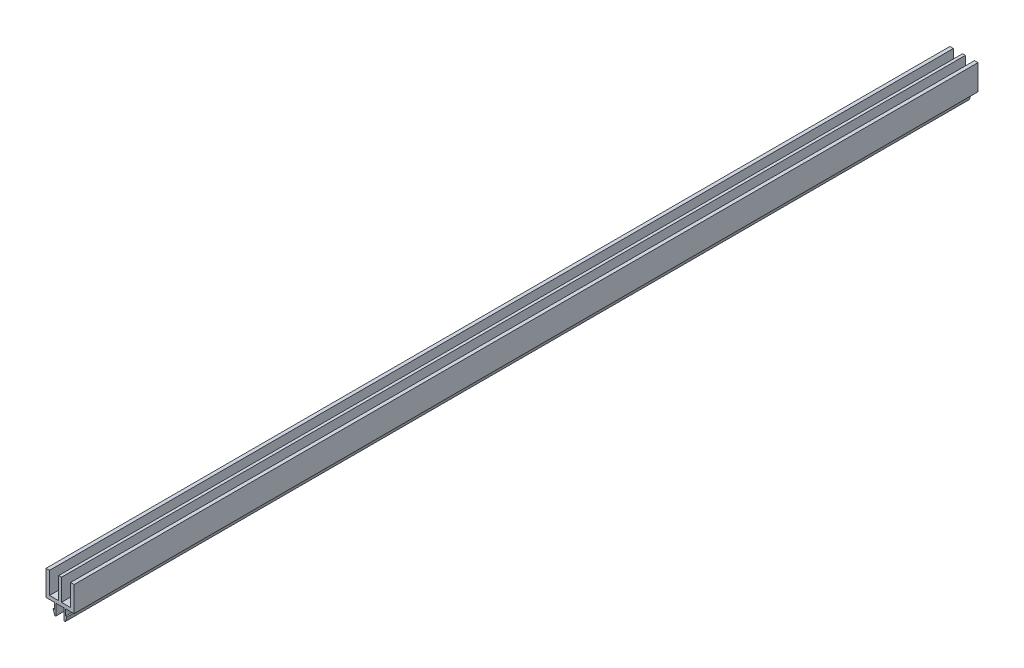
SolidWorks part; units mm, degrees
ref_plane "Plan de face" through (0, 0, 0) normal (0, 0, 1) x (1, 0, 0)
ref_plane "Plan de dessus" through (0, 0, 0) normal (0, 1, 0) x (1, 0, 0)
ref_plane "Plan de droite" through (0, 0, 0) normal (1, 0, 0) x (0, 0, -1)
ref_plane "Plan1" through (0, 0, 50) normal (0, 0, 1) x (1, 0, 0)
sketch "Esquisse1" plane through (0, 0, 50) normal (0, 0, 1) x (1, 0, 0)
  line L0 (-1, 2.5) -> (-7.5, 2.5)
  line L1 (-7.5, 2.5) -> (-7.5, 18)
  line L2 (-7.5, 18) -> (-10, 18)
  line L3 (-10, 18) -> (-10, 0)
  line L4 (-10, 0) -> (-4, 0)
  line L5 (-4, 0) -> (-4, -4.5)
  line L6 (-4, -4.5) -> (-5, -4.5)
  line L7 (-5, -4.5) -> (-3.75, -8)
  line L8 (-3.75, -8) -> (-3, -8)
  line L9 (-3, -8) -> (-3, 0)
  line L10 (-3, 0) -> (3, 0)
  line L11 (3, 0) -> (3, -8)
  line L12 (3, -8) -> (3.75, -8)
  line L13 (3.75, -8) -> (5, -4.5)
  line L14 (5, -4.5) -> (4, -4.5)
  line L15 (4, -4.5) -> (4, 0)
  line L16 (4, 0) -> (10, 0)
  line L17 (10, 0) -> (10, 18)
  line L18 (10, 18) -> (7.5, 18)
  line L19 (7.5, 18) -> (7.5, 2.5)
  line L20 (7.5, 2.5) -> (1, 2.5)
  line L21 (1, 2.5) -> (1, 18)
  line L22 (1, 18) -> (-1, 18)
  line L23 (-1, 18) -> (-1, 2.5)
extrude "Boss.-Extru.1" add sketch "Esquisse1" against normal blind 644
